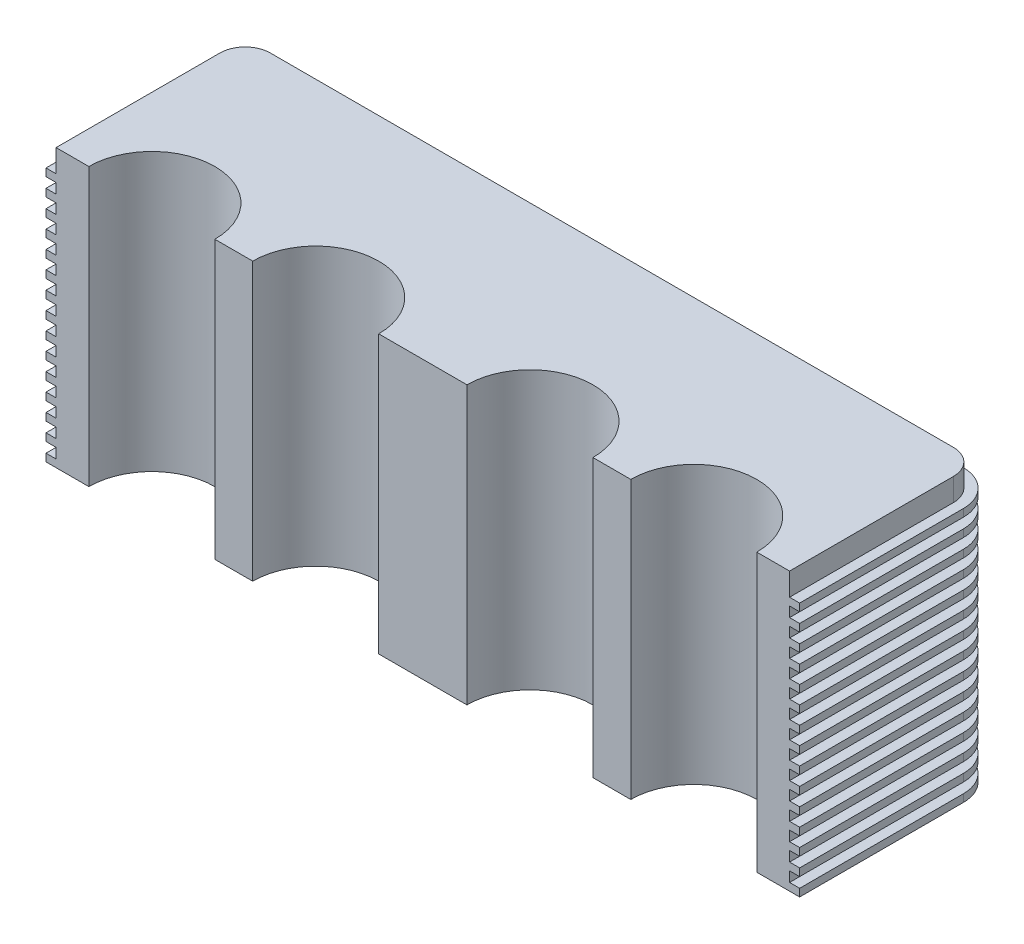
SolidWorks part; units mm, degrees
ref_plane "Front Plane" through (0, 0, 0) normal (0, 0, 1) x (1, 0, 0)
ref_plane "Top Plane" through (0, 0, 0) normal (0, 1, 0) x (1, 0, 0)
ref_plane "Right Plane" through (0, 0, 0) normal (1, 0, 0) x (0, 0, -1)
sketch "Sketch2" plane through (0, 0, 0) normal (0, 1, 0) x (1, 0, 0)
  line L0 (145.5, 0) -> (145.5, 75) construction
  line L1 (0, 0) -> (13, 0)
  line L2 (0, 0) -> (0, 65)
  line L3 (10, 75) -> (281, 75)
  line L4 (291, 0) -> (291, 65)
  line L5 (278, 0) -> (291, 0)
  line L6 (213, 0) -> (228, 0)
  line L7 (128, 0) -> (163, 0)
  line L8 (63, 0) -> (78, 0)
  arc A0 (291, 65) -> (281, 75) centre (281, 65) ccw
  arc A1 (10, 75) -> (0, 65) centre (10, 65) ccw
  arc A2 (278, 0) -> (228, 0) centre (253, 0) ccw
  arc A3 (213, 0) -> (163, 0) centre (188, 0) ccw
  arc A4 (13, 0) -> (63, 0) centre (38, 0) cw
  arc A5 (78, 0) -> (128, 0) centre (103, 0) cw
  dimension "D1" = 10
  dimension "D4" = 25
  dimension "D6" = 50
  dimension "D2" = 271
  dimension "D3" = 65
  dimension "D5" = 13
  dimension "D7" = 15
extrude "Boss-Extrude1" add sketch "Sketch2" along normal blind 110
sketch "Sketch4" plane through (0, 0, 0) normal (0, 1, 0) x (1, 0, 0)
  line L23 (-4, 65) -> (-4, -4) construction
  line L24 (295, 0) -> (295, 65)
  line L25 (281, 79) -> (10, 79)
  line L26 (-4, 65) -> (-4, 0)
  line L27 (295, -4) -> (295, 65) construction
  line L28 (0, 0) -> (-4, 0)
  line L29 (291, 0) -> (295, 0)
  line L31 (0, 65) -> (0, 0)
  line L32 (0, 0) -> (13, 0)
  line L33 (63, 0) -> (78, 0)
  line L34 (128, 0) -> (163, 0)
  line L35 (213, 0) -> (228, 0)
  line L36 (278, 0) -> (291, 0)
  line L37 (291, 0) -> (291, 65)
  line L38 (281, 75) -> (10, 75)
  line L39 (0, 65) -> (0, 0)
  line L40 (0, 0) -> (13, 0)
  line L41 (63, 0) -> (78, 0)
  line L42 (128, 0) -> (163, 0)
  line L43 (213, 0) -> (228, 0)
  line L44 (278, 0) -> (291, 0)
  line L45 (291, 0) -> (291, 65)
  line L46 (281, 75) -> (10, 75)
  line L47 (-4, -4) -> (13, -4) construction
  line L48 (278, -4) -> (295, -4) construction
  arc A6 (295, 65) -> (281, 79) centre (281, 65) ccw
  arc A7 (10, 79) -> (-4, 65) centre (10, 65) ccw
  arc A12 (63, 0) -> (13, 0) centre (38, 0) ccw
  arc A13 (128, 0) -> (78, 0) centre (103, 0) ccw
  arc A14 (213, 0) -> (163, 0) centre (188, 0) ccw
  arc A15 (278, 0) -> (228, 0) centre (253, 0) ccw
  arc A16 (291, 65) -> (281, 75) centre (281, 65) ccw
  arc A17 (10, 75) -> (0, 65) centre (10, 65) ccw
  arc A18 (63, 0) -> (13, 0) centre (38, 0) ccw
  arc A19 (128, 0) -> (78, 0) centre (103, 0) ccw
  arc A20 (213, 0) -> (163, 0) centre (188, 0) ccw
  arc A21 (278, 0) -> (228, 0) centre (253, 0) ccw
  arc A22 (291, 65) -> (281, 75) centre (281, 65) ccw
  arc A23 (10, 75) -> (0, 65) centre (10, 65) ccw
  dimension "D1" = 0
  dimension "D2" = 4
extrude "Boss-Extrude3" add sketch "Sketch4" along normal blind 3 contours A23 L46 A22 L45 L29 L24 A6 L25 A7 L26 L28 L39
pattern_linear "LPattern1" count 15 spacing 7 along (0, 1, 0) of "Boss-Extrude3"
